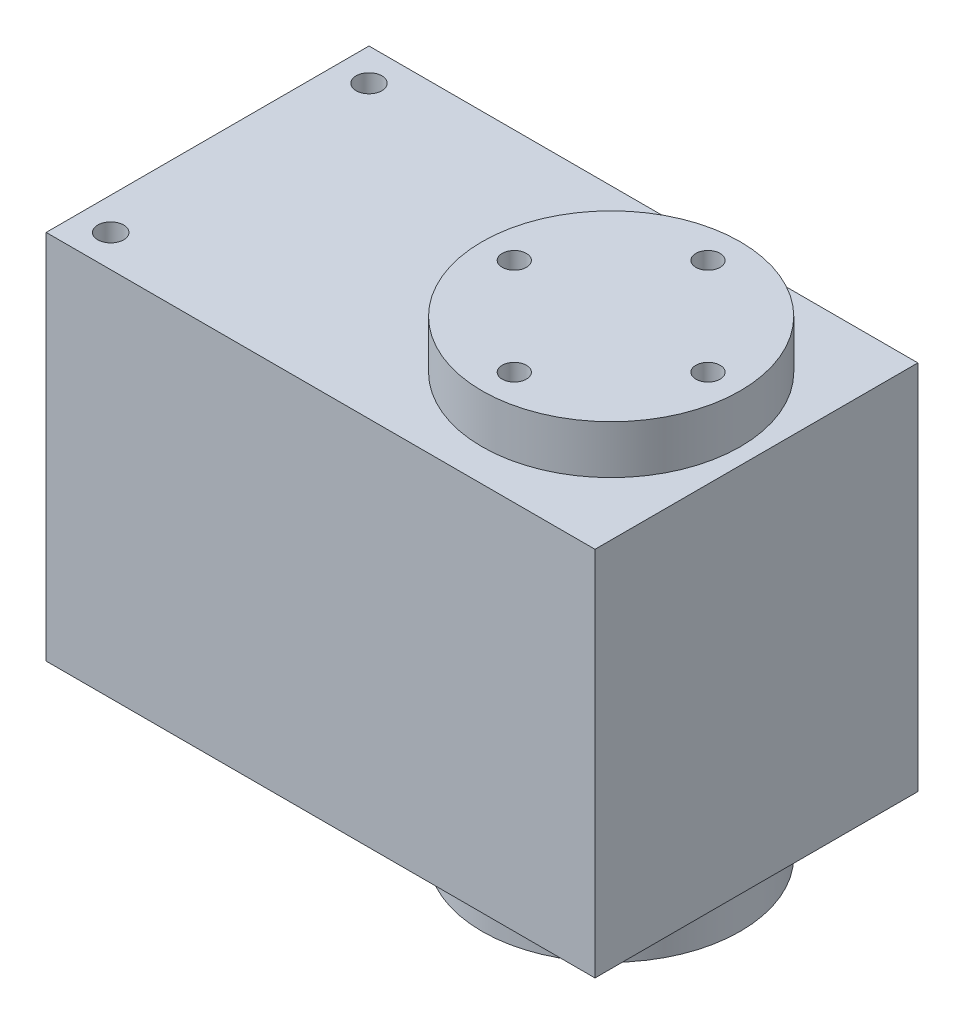
SolidWorks part; units mm, degrees
ref_plane "前视基准面" through (0, 0, 0) normal (0, 0, 1) x (1, 0, 0)
ref_plane "上视基准面" through (0, 0, 0) normal (0, 1, 0) x (1, 0, 0)
ref_plane "右视基准面" through (0, 0, 0) normal (1, 0, 0) x (0, 0, -1)
sketch "草图1" plane through (0, 0, 0) normal (1, 0, 0) x (0, 0, -1)
  line L1 (-10, 11.5) -> (10, 11.5)
  line L2 (-10, 11.5) -> (-10, -11.5)
  line L3 (-10, -11.5) -> (10, -11.5)
  line L4 (10, 11.5) -> (10, -11.5)
  line L5 (-10, 11.5) -> (10, -11.5) construction
  line L6 (-10, -11.5) -> (10, 11.5) construction
  point P0 (0, 0)
  dimension "D1" = 20
  dimension "D2" = 23
extrude "凸台-拉伸1" add sketch "草图1" along normal blind 34
sketch "草图2" plane through (0, -11.5, 0) normal (0, -1, 0) x (-1, 0, 0)
  line L0 (-2, -9.0564) -> (-2, 8.6704)
  line L1 (0, -10) -> (0, 10) construction
  line L2 (-0.5586, -8) -> (-8.737, -8)
  line L3 (-34, -10) -> (0, -10) construction
  line L4 (0, 0) -> (-34, 0)
  line L5 (-34, -10) -> (-34, 10) construction
  circle A0 centre (-2, -8) radius 0.8
  circle A1 centre (-2, 8) radius 0.8
  dimension "D1" = 2
  dimension "D2" = 2
extrude "切除-拉伸1" cut sketch "草图2" against normal blind 34 and the other way blind 10
sketch "草图3" plane through (0, 11.5, 0) normal (0, 1, 0) x (1, 0, 0)
  line L0 (34, 0) -> (25, 0)
  line L1 (34, 10) -> (34, -10) construction
  circle A0 centre (25, 0) radius 8
  dimension "D1" = 9
extrude "凸台-拉伸2" add sketch "草图3" along normal blind 3
ref_plane "基准面1" through (0, 0, 0) normal (0, 1, 0) x (1, 0, 0)
mirror "镜向1" about plane through (0, 0, 0) normal (0, 1, 0) of "凸台-拉伸2"
sketch "草图4" plane through (0, 14.5, 0) normal (0, 1, 0) x (1, 0, 0)
  circle A2 centre (25, -6) radius 0.75
  circle A3 centre (45.5, 14.5) radius 0.75
  circle A4 centre (25, 35) radius 0.75
  circle A5 centre (4.5, 14.5) radius 0.75
  circle A6 centre (19, 0) radius 0.75
  circle A7 centre (25, 6) radius 0.75
  circle A8 centre (31, 0) radius 0.75
  point P12 (25, 14.5)
  point P19 (25, 0)
  dimension "D1" = 4
  dimension "D3" = 12
  dimension "D2" = 4
extrude "切除-拉伸2" cut sketch "草图4" against normal blind 3
mirror "镜向2" about plane through (0, 0, 0) normal (0, 1, 0) of "切除-拉伸2"
